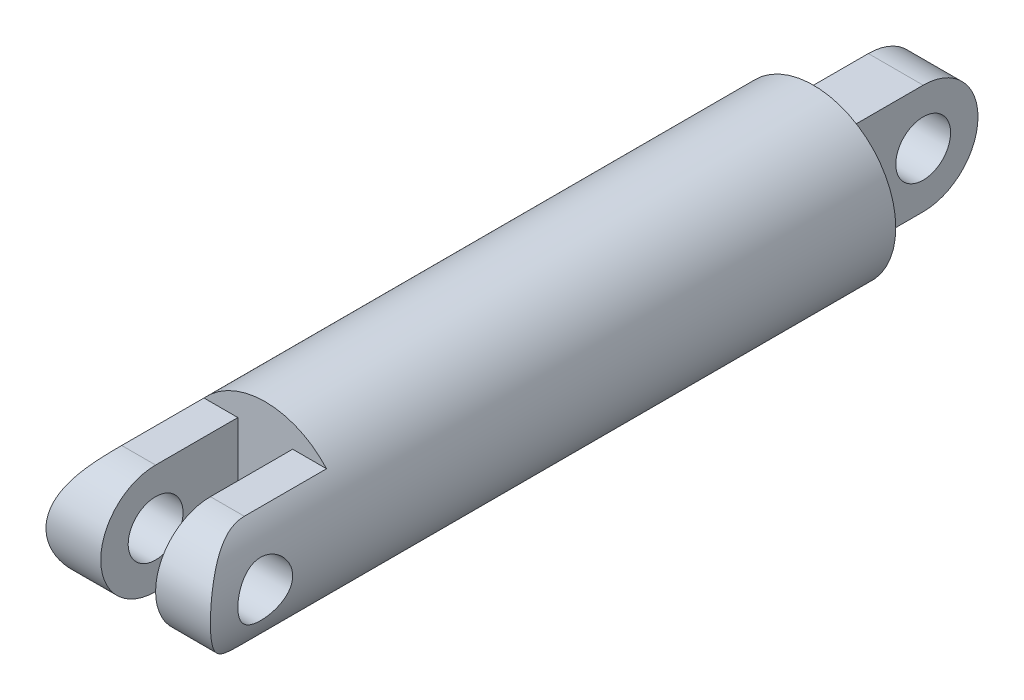
SolidWorks part; units mm, degrees
ref_plane "Alzado" through (0, 0, 0) normal (0, 0, 1) x (1, 0, 0)
ref_plane "Planta" through (0, 0, 0) normal (0, 1, 0) x (1, 0, 0)
ref_plane "Vista lateral" through (0, 0, 0) normal (1, 0, 0) x (0, 0, -1)
sketch "Croquis1" plane through (0, 0, 0) normal (0, 0, 1) x (1, 0, 0)
  circle A0 centre (0, 0) radius 7.5
  dimension "D1" = 15
extrude "Saliente-Extruir1" add sketch "Croquis1" along normal blind 50
sketch "Croquis4" plane through (0, 0, 0) normal (0, 0, -1) x (-1, 0, 0)
  line L0 (0, 8.25) -> (0, -8.25) construction
  line L1 (2.5, 5) -> (-2.5, 5)
  line L2 (2.5, 5) -> (2.5, -5)
  line L3 (2.5, -5) -> (-2.5, -5)
  line L4 (-2.5, 5) -> (-2.5, -5)
  line L5 (2.5, 5) -> (-2.5, -5) construction
  line L6 (2.5, -5) -> (-2.5, 5) construction
  point P0 (0, 0)
  dimension "D1" = 5
  dimension "D2" = 10
extrude "Saliente-Extruir2" add sketch "Croquis4" along normal blind 12.5
sketch "Croquis5" plane through (-2.5, 0, 0) normal (-1, 0, 0) x (0, 0, 1)
  line L0 (-12.5, 5) -> (0, 5) construction
  line L1 (-12.5, -5) -> (-12.5, 5) construction
  line L2 (-12.5, -5) -> (0, -5) construction
  circle A0 centre (-7.5, 0) radius 2.5
  arc A1 (-7.5, 5) -> (-7.5, -5) centre (-7.5, 0) ccw
  line M2 (0, 5) -> (-12.5, 5)
  line M3 (-12.5, 5) -> (-12.5, -5)
  line M4 (-12.5, -5) -> (0, -5)
  dimension "D2" = 5
  dimension "D3" = 5
  dimension "D1" = 5
extrude "Cortar-Extruir1" cut sketch "Croquis5" against normal blind 5 contours A1 M3 M4 | A1 M2 M3 | A0
sketch "Croquis9" plane through (0, 0, 0) normal (1, 0, 0) x (0, 0, -1)
  line L1 (-50, 5) -> (-62.5, 5)
  line L2 (-50, 5) -> (-50, -5)
  line L3 (-50, -5) -> (-62.5, -5)
  line L4 (-62.5, 5) -> (-62.5, -5)
  line L5 (8.25, 0) -> (-8.25, 0) construction
  line L6 (-50, 7.5) -> (-50, -7.5) construction
  circle A0 centre (-57.5, 0) radius 2.5
  arc A1 (-57.5, 5) -> (-57.5, -5) centre (-57.5, 0) ccw
  point P17 (-50, 0)
  dimension "D3" = 5
  dimension "D1" = 10
  dimension "D2" = 12.5
  dimension "D4" = 5
  dimension "D5" = 5
extrude "Saliente-Extruir4" add sketch "Croquis9" along normal blind 7.5 and the other way blind 7.5 contours L1 A1 L3 L2 A0
sketch "Croquis10" plane through (0, 0, 50) normal (0, 0, 1) x (1, 0, 0)
  line L1 (2.5, 5) -> (-2.5, 5)
  line L2 (2.5, 5) -> (2.5, -5)
  line L3 (2.5, -5) -> (-2.5, -5)
  line L4 (-2.5, 5) -> (-2.5, -5)
  line L5 (2.5, 5) -> (-2.5, -5) construction
  line L6 (2.5, -5) -> (-2.5, 5) construction
  line L7 (7.5, 5) -> (-7.5, 5)
  line L8 (7.5, 5) -> (7.5, -5)
  line L9 (7.5, -5) -> (-7.5, -5)
  line L10 (-7.5, 5) -> (-7.5, -5)
  line L11 (7.5, 5) -> (-7.5, -5) construction
  line L12 (7.5, -5) -> (-7.5, 5) construction
  point P0 (0, 0)
  point P6 (0, 0)
  dimension "D1" = 5
  dimension "D2" = 15
  dimension "D3" = 10
extrude "Cortar-Extruir2" cut sketch "Croquis10" along normal blind 12.5
sketch "Croquis11" plane through (0, 0, 50) normal (0, 0, 1) x (1, 0, 0)
  circle A0 centre (0, 0) radius 7.5
  circle A1 centre (0, 0) radius 10
  arc A2 (-5.5902, -5) -> (5.5902, -5) centre (0, 0) ccw construction
  dimension "D1" = 20
extrude "Cortar-Extruir3" cut sketch "Croquis11" along normal blind 12.5
